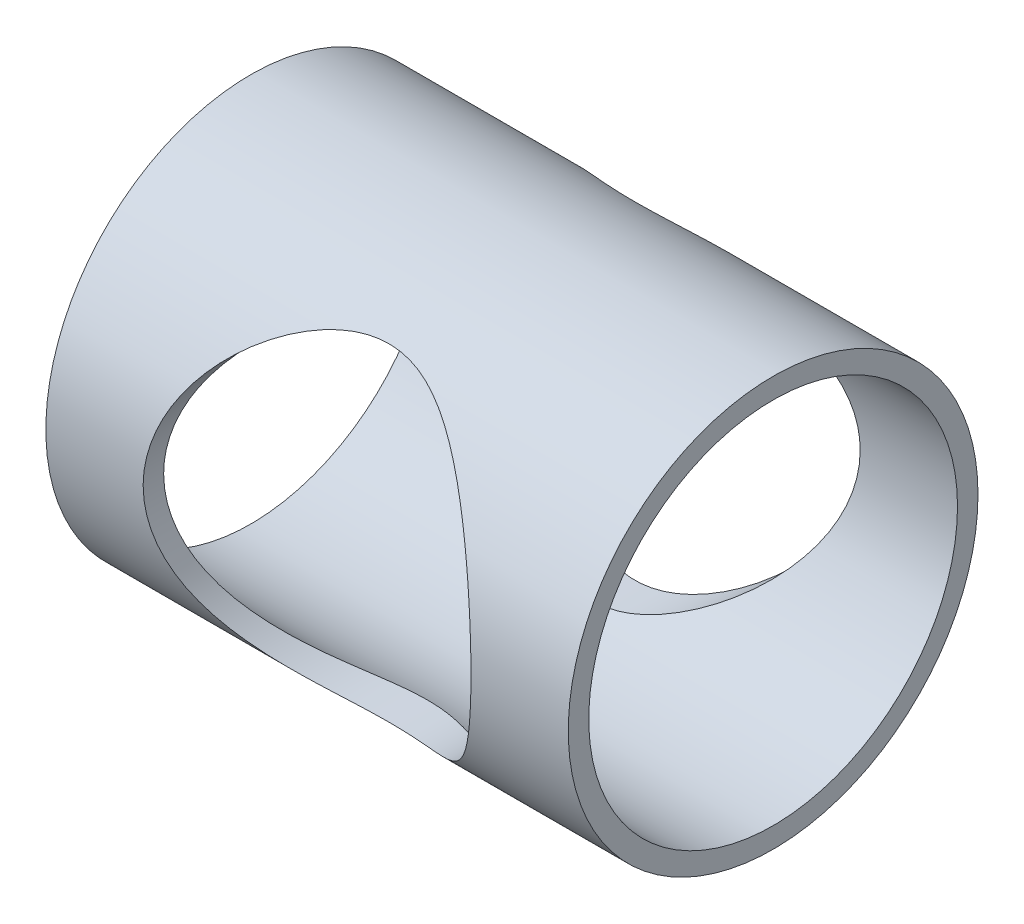
SolidWorks part; units mm, degrees
material "6061-T6 (SS)"
ref_plane "Front Plane" through (0, 0, 0) normal (0, 0, 1) x (1, 0, 0)
ref_plane "Top Plane" through (0, 0, 0) normal (0, 1, 0) x (1, 0, 0)
ref_plane "Right Plane" through (0, 0, 0) normal (1, 0, 0) x (0, 0, -1)
sketch "Sketch1" plane through (0, 0, 0) normal (1, 0, 0) x (0, 0, -1)
  circle A0 centre (0, 0) radius 31.75
  dimension "D1" = 63.5
extrude "Boss-Extrude1" add sketch "Sketch1" along normal mid plane 80.9625
shell "Shell1" thickness 3.175
sketch "Sketch2" plane through (0, 0, 0) normal (0, 0, 1) x (1, 0, 0)
  circle A0 centre (0, 0) radius 25.4
  dimension "D1" = 50.8
extrude "Cut-Extrude1" cut sketch "Sketch2" along normal through all both and the other way through all
